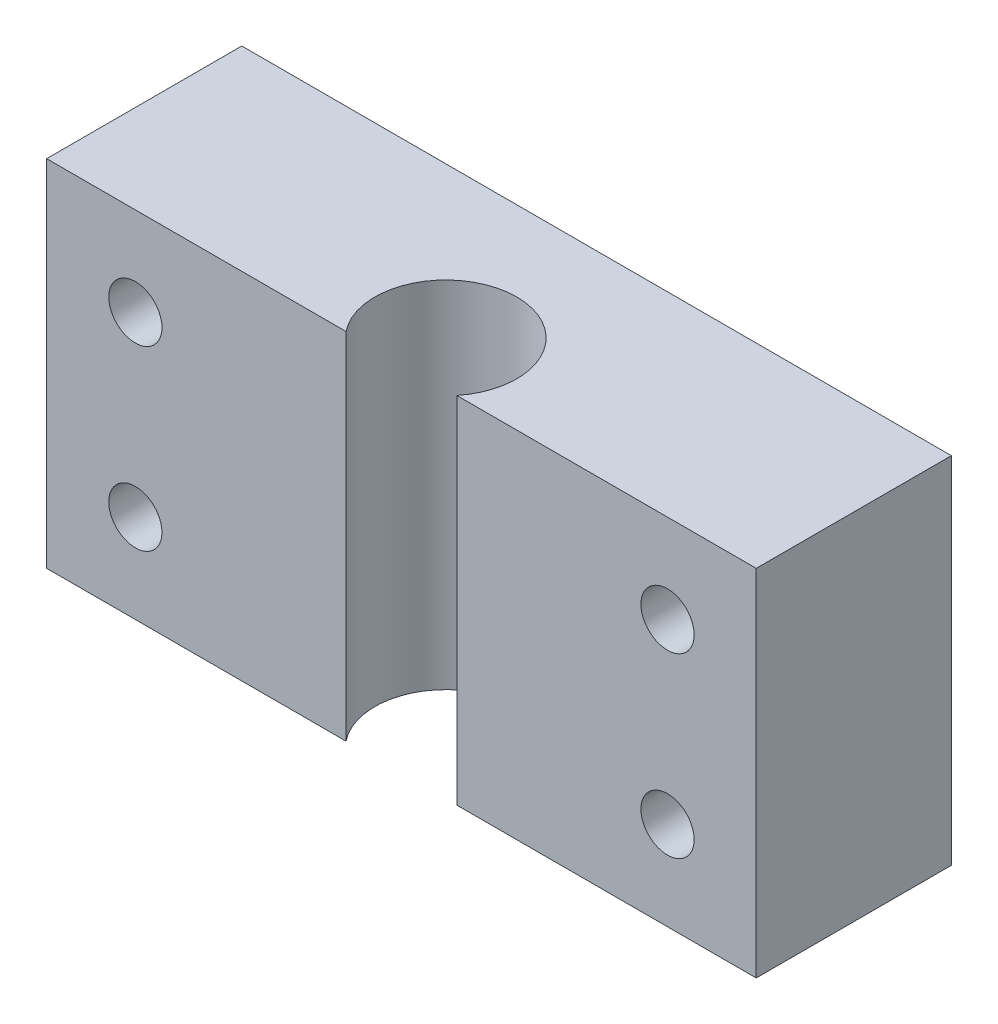
SolidWorks part; units mm, degrees
ref_plane "Piano frontale" through (0, 0, 0) normal (0, 0, 1) x (1, 0, 0)
ref_plane "Piano superiore" through (0, 0, 0) normal (0, 1, 0) x (1, 0, 0)
ref_plane "Piano destro" through (0, 0, 0) normal (1, 0, 0) x (0, 0, -1)
sketch "Schizzo1" plane through (0, 0, 0) normal (0, 0, 1) x (1, 0, 0)
  line L1 (-40, 20) -> (40, 20)
  line L2 (-40, 20) -> (-40, -20)
  line L3 (-40, -20) -> (40, -20)
  line L4 (40, 20) -> (40, -20)
  line L5 (-40, 20) -> (40, -20) construction
  line L6 (-40, -20) -> (40, 20) construction
  point P0 (0, 0)
  dimension "D1" = 40
  dimension "D2" = 80
extrude "Estrusione-Estrusione1" add sketch "Schizzo1" along normal blind 22
sketch "Schizzo2" plane through (0, -20, 0) normal (0, -1, 0) x (1, 0, 0)
  line L0 (0, 0) -> (0, 50000) construction
  line L1 (-40, 0) -> (40, 0) construction
  line L2 (-40, 22) -> (40, 22) construction
  circle A0 centre (0, 17) radius 8
  point P4 (0, 0)
  dimension "D2" = 16
  dimension "D1" = 5
extrude "Taglio-Estrusione1" cut sketch "Schizzo2" against normal through all
sketch "Schizzo3" plane through (0, 0, 22) normal (0, 0, 1) x (1, 0, 0)
  line L0 (0, 0) -> (0, 50000) construction
  line L1 (-30, -8.5035) -> (-30, 49991.4965) construction
  line L2 (0, 0) -> (-40, 0) construction
  line L3 (-40, 20) -> (-40, -20) construction
  line L5 (-40, 10) -> (49960, 10) construction
  line L6 (-40, -10) -> (49960, -10) construction
  circle A0 centre (-30, 10) radius 3
  circle A1 centre (-30, -10) radius 3
  circle A2 centre (30, -10) radius 3
  circle A3 centre (30, 10) radius 3
  dimension "D4" = 6
  dimension "D1" = 30
  dimension "D2" = 10
  dimension "D3" = 10
extrude "Taglio-Estrusione2" cut sketch "Schizzo3" against normal through all
